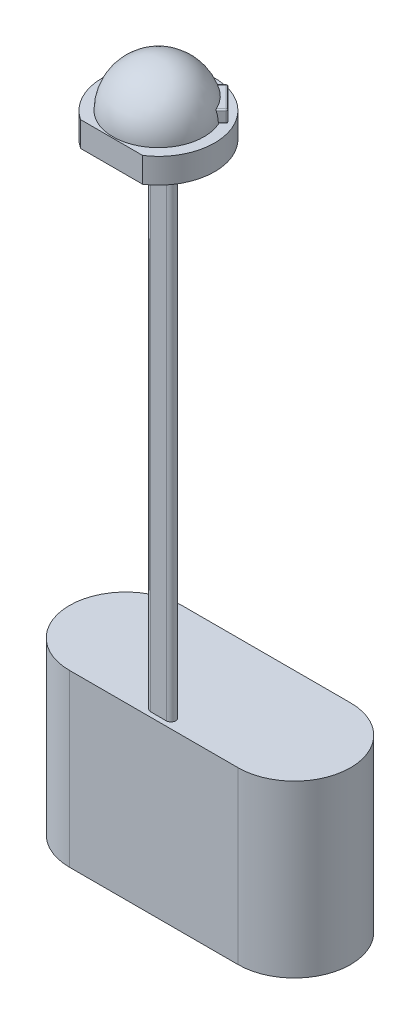
SolidWorks part; units mm, degrees
ref_plane "Front Plane" through (0, 0, 0) normal (0, 0, 1) x (1, 0, 0)
ref_plane "Top Plane" through (0, 0, 0) normal (0, 1, 0) x (1, 0, 0)
ref_plane "Right Plane" through (0, 0, 0) normal (1, 0, 0) x (0, 0, -1)
sketch "Sketch1" plane through (0, -8.2414, 0) normal (0, 1, 0) x (1, 0, 0)
  line L0 (-124.7799, -7) -> (145.2201, -7) construction
  line L1 (-124.7799, 83) -> (145.2201, 83)
  line L2 (-124.7799, -97) -> (145.2201, -97)
  line L3 (-159.7799, 93) -> (-214.7799, 93) construction
  line L5 (260.2201, -82) -> (260.2201, 68) construction
  line L7 (-124.7799, 80) -> (145.2201, 80)
  line L8 (-124.7799, -94) -> (145.2201, -94)
  arc A0 (-124.7799, 83) -> (-124.7799, -97) centre (-124.7799, -7) ccw
  arc A1 (145.2201, -97) -> (145.2201, 83) centre (145.2201, -7) ccw
  arc A2 (145.2201, -94) -> (145.2201, 80) centre (145.2201, -7) ccw
  arc A3 (-124.7799, 80) -> (-124.7799, -94) centre (-124.7799, -7) ccw
  point P2 (10.2201, -7)
  dimension "D5" = 3
  dimension "D1" = 100
  dimension "D2" = 270
  dimension "D3" = 90
  dimension "D4" = 250
extrude "Boss-Extrude1" add sketch "Sketch1" along normal blind 270
sketch "Sketch4" plane through (0, 261.7586, 0) normal (0, 1, 0) x (1, 0, 0)
  line L2 (-124.7799, -97) -> (145.2201, -97)
  line L3 (145.2201, 83) -> (-124.7799, 83)
  line L4 (-124.7799, -97) -> (145.2201, -97)
  line L5 (145.2201, 83) -> (-124.7799, 83)
  arc A2 (-124.7799, 83) -> (-124.7799, -97) centre (-124.7799, -7) ccw
  arc A3 (145.2201, -97) -> (145.2201, 83) centre (145.2201, -7) ccw
  arc A4 (-124.7799, 83) -> (-124.7799, -97) centre (-124.7799, -7) ccw
  arc A5 (145.2201, -97) -> (145.2201, 83) centre (145.2201, -7) ccw
  dimension "D1" = 0
extrude "Boss-Extrude2" add sketch "Sketch4" along normal blind 3
sketch "Sketch5" plane through (0, 264.7586, 0) normal (0, 1, 0) x (1, 0, 0)
  line L0 (22.7201, -82) -> (-2.2799, -82) construction
  line L1 (22.7201, -89.5) -> (-2.2799, -89.5)
  line L2 (22.7201, -74.5) -> (-2.2799, -74.5)
  line L3 (145.2201, 83) -> (-124.7799, 83) construction
  line L4 (10.2201, -89.5) -> (10.2201, -74.5) construction
  line L5 (-124.7799, -97) -> (145.2201, -97) construction
  arc A0 (22.7201, -89.5) -> (22.7201, -74.5) centre (22.7201, -82) ccw
  arc A1 (-2.2799, -74.5) -> (-2.2799, -89.5) centre (-2.2799, -82) ccw
  point P2 (10.2201, -82)
  dimension "D1" = 165
  dimension "D2" = 25
  dimension "D3" = 15
  dimension "D4" = 135
extrude "Boss-Extrude3" add sketch "Sketch5" along normal blind 800
sketch "Sketch6" plane through (0, 1064.7586, 0) normal (0, 1, 0) x (1, 0, 0)
  line L0 (-2.2799, -89.5) -> (22.7201, -89.5) construction
  line L1 (100.2201, -89.5) -> (-79.7799, -89.5) construction
  line L2 (59.9694, -164.5) -> (-39.5293, -164.5)
  line L3 (10.2201, -89.5) -> (10.2201, -164.5) construction
  arc A0 (59.9694, -164.5) -> (-39.5293, -164.5) centre (10.2201, -89.5) ccw
  dimension "D2" = 180
  dimension "D1" = 75
extrude "Boss-Extrude4" add sketch "Sketch6" along normal blind 40
sketch "Sketch7" plane through (0, 1104.7586, 0) normal (0, 1, 0) x (1, 0, 0)
  line L1 (10.2201, -18.5) -> (10.2201, -16.5)
  line L2 (10.2201, -160.5) -> (10.2201, -162.5)
  line L3 (10.2201, -89.5) -> (10.2201, -16.5) construction
  arc A3 (10.2201, -18.5) -> (10.2201, -160.5) centre (10.2201, -89.5) ccw
  arc A4 (43.3863, -139.5) -> (-22.9462, -139.5) centre (10.2201, -89.5) ccw
  arc A5 (43.3863, -139.5) -> (-22.9462, -139.5) centre (10.2201, -89.5) ccw construction
  arc A6 (10.2201, -16.5) -> (10.2201, -162.5) centre (10.2201, -89.5) ccw
  circle A8 centre (10.2201, -89.5) radius 73 construction
  circle A9 centre (10.2201, -89.5) radius 71 construction
  point P2 (78.1177, -68.7416)
  point P7 (83.2201, -89.5)
  dimension "D1" = 30
  dimension "D2" = 142
  dimension "D3" = 2
revolve "Revolve1" add sketch "Sketch7" angle 180 about L3
sketch "Sketch9" plane through (0, 1104.7586, 0) normal (0, 1, 0) x (1, 0, 0)
  line L0 (100.2201, -89.5) -> (-79.7799, -89.5) construction
  line L1 (-79.7799, -89.5) -> (10.2201, 0.5) construction
  line L2 (10.2201, 0.5) -> (100.2201, -89.5) construction
  line L3 (73.8597, -63.1396) -> (84.4663, -52.533)
  line L4 (84.4663, -52.533) -> (49.1109, -17.1776)
  line L5 (49.1109, -17.1776) -> (38.5043, -27.7842)
  line L6 (38.5043, -27.7842) -> (73.8597, -63.1396)
  line L7 (-18.0642, -27.7842) -> (-28.6708, -17.1776)
  line L8 (-28.6708, -17.1776) -> (-64.0261, -52.533)
  line L9 (-64.0261, -52.533) -> (-53.4195, -63.1396)
  line L10 (-53.4195, -63.1396) -> (-18.0642, -27.7842)
  arc A0 (59.9694, -164.5) -> (-39.5293, -164.5) centre (10.2201, -89.5) ccw construction
  dimension "D1" = 15
  dimension "D2" = 15
  dimension "D3" = 50
  dimension "D4" = 50
  dimension "D5" = 40
  dimension "D6" = 40
extrude "Boss-Extrude5" add sketch "Sketch9" along normal blind 20 separate body
fillet "Fillet1" radius 2 10 edges at (73.8597, 1114.7586, 63.1396) (79.163, 1124.7586, 57.8363) (79.163, 1104.7586, 57.8363) (43.8076, 1124.7586, 22.4809) (38.5043, 1114.7586, 27.7842) (43.8076, 1104.7586, 22.4809) (84.4663, 1114.7586, 52.533) (66.7886, 1124.7586, 34.8553) (49.1109, 1114.7586, 17.1776) (66.7886, 1104.7586, 34.8553)
fillet "Fillet2" radius 2 10 edges at (-58.7228, 1124.7586, 57.8363) (-53.4195, 1114.7586, 63.1396) (-58.7228, 1104.7586, 57.8363) (-18.0642, 1114.7586, 27.7842) (-23.3675, 1124.7586, 22.4809) (-23.3675, 1104.7586, 22.4809) (-28.6708, 1114.7586, 17.1776) (-46.3485, 1124.7586, 34.8553) (-64.0261, 1114.7586, 52.533) (-46.3485, 1104.7586, 34.8553)
